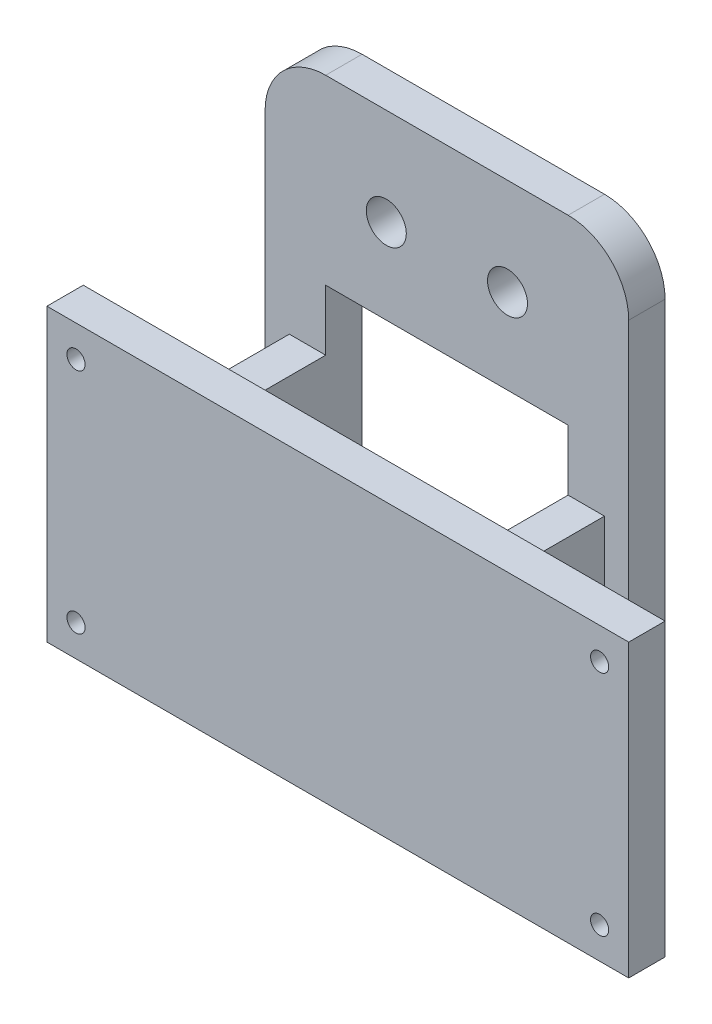
SolidWorks part; units mm, degrees
ref_plane "前视基准面" through (0, 0, 0) normal (0, 0, 1) x (1, 0, 0)
ref_plane "上视基准面" through (0, 0, 0) normal (0, 1, 0) x (1, 0, 0)
ref_plane "右视基准面" through (0, 0, 0) normal (1, 0, 0) x (0, 0, -1)
sketch "草图1" plane through (0, 0, 0) normal (0, 0, 1) x (1, 0, 0)
  line L0 (-9.1846, -30.6462) -> (20.8154, -30.6462)
  line L1 (-9.1846, 4.3538) -> (20.8154, 4.3538)
  line L2 (-9.1846, 4.3538) -> (-9.1846, -30.6462)
  line L4 (20.8154, 4.3538) -> (20.8154, -30.6462)
  circle A0 centre (0.8154, -3.6462) radius 1.65
  circle A1 centre (10.8154, -3.6462) radius 1.65
  dimension "D3" = 3.3
  dimension "D4" = 3.3
  dimension "D5" = 10
  dimension "D6" = 10
  dimension "D8" = 8
  dimension "D9" = 8
  dimension "D1" = 30
  dimension "D2" = 35
extrude "凸台-拉伸1" add sketch "草图1" along normal blind 3
sketch "草图2" plane through (0, 0, 3) normal (0, 0, 1) x (1, 0, 0)
  line L0 (-9.1846, 4.3538) -> (-9.1846, -30.6462) construction
  line L5 (20.8154, 4.3538) -> (-9.1846, 4.3538) construction
  line L6 (-9.1846, -30.6462) -> (20.8154, -30.6462) construction
  line L7 (-4.1846, -30.6462) -> (15.8154, -30.6462)
  line L8 (-4.1846, -30.6462) -> (-4.1846, -10.6462)
  line L9 (-4.1846, -10.6462) -> (15.8154, -10.6462)
  line L10 (15.8154, -30.6462) -> (15.8154, -10.6462)
  line L11 (5.8154, 4.3538) -> (5.8154, -30.6462) construction
  line L12 (-9.1846, -0.6462) -> (-9.1846, 4.3538)
  line L13 (-9.1846, 4.3538) -> (-4.1846, 4.3538)
  line L14 (20.8154, -0.6462) -> (20.8154, 4.3538)
  line L15 (20.8154, 4.3538) -> (15.8154, 4.3538)
  arc A0 (-9.1846, -0.6462) -> (-4.1846, 4.3538) centre (-4.1846, -0.6462) cw
  arc A1 (20.8154, -0.6462) -> (15.8154, 4.3538) centre (15.8154, -0.6462) ccw
  dimension "D1" = 5
  dimension "D2" = 5
  dimension "D3" = 5
  dimension "D4" = 20
  dimension "D5" = 20
  dimension "D6" = 5
extrude "切除-拉伸1" cut sketch "草图2" against normal blind 6
sketch "草图3" plane through (0, 0, 3) normal (0, 0, 1) x (1, 0, 0)
  line L1 (-4.1846, -30.6462) -> (-7.1846, -30.6462)
  line L2 (-4.1846, -30.6462) -> (-4.1846, -15.6462)
  line L3 (-4.1846, -15.6462) -> (-7.1846, -15.6462)
  line L4 (-7.1846, -30.6462) -> (-7.1846, -15.6462)
  line L5 (15.8154, -30.6462) -> (18.8154, -30.6462)
  line L6 (15.8154, -30.6462) -> (15.8154, -15.6462)
  line L7 (15.8154, -15.6462) -> (18.8154, -15.6462)
  line L8 (18.8154, -30.6462) -> (18.8154, -15.6462)
  dimension "D1" = 15
  dimension "D2" = 3
  dimension "D3" = 3
  dimension "D4" = 15
extrude "凸台-拉伸2" add sketch "草图3" along normal blind 6
sketch "草图4" plane through (0, 0, 9) normal (0, 0, 1) x (1, 0, 0)
  line L0 (-7.1846, -15.6462) -> (-7.1846, -30.6462) construction
  line L1 (-18.1846, -14.6462) -> (29.8154, -14.6462)
  line L2 (-18.1846, -14.6462) -> (-18.1846, -38.6462)
  line L3 (-18.1846, -38.6462) -> (29.8154, -38.6462)
  line L4 (29.8154, -14.6462) -> (29.8154, -38.6462)
  line L5 (18.8154, -30.6462) -> (18.8154, -15.6462) construction
  line L6 (-4.1846, -15.6462) -> (-7.1846, -15.6462) construction
  dimension "D1" = 48
  dimension "D2" = 26
  dimension "D3" = 11
  dimension "D4" = 24
  dimension "D5" = 1
extrude "凸台-拉伸3" add sketch "草图4" along normal blind 3
sketch "草图6" plane through (0, 0, 12) normal (0, 0, 1) x (1, 0, 0)
  line L0 (5.8154, -14.6462) -> (5.8154, -38.6462) construction
  line L1 (29.8154, -14.6462) -> (-18.1846, -14.6462) construction
  line L2 (-18.1846, -38.6462) -> (29.8154, -38.6462) construction
  line L4 (-17.0346, -37.2962) -> (28.6654, -37.2962) construction
  line L5 (-17.0346, -37.2962) -> (-17.0346, -15.9962) construction
  line L6 (-17.0346, -15.9962) -> (28.6654, -15.9962) construction
  line L7 (28.6654, -37.2962) -> (28.6654, -15.9962) construction
  line L8 (-17.0346, -37.2962) -> (28.6654, -15.9962) construction
  line L9 (-17.0346, -15.9962) -> (28.6654, -37.2962) construction
  circle A0 centre (-15.7846, -17.2462) radius 0.75
  circle A1 centre (-15.7846, -36.0462) radius 0.75
  circle A2 centre (27.4154, -36.0462) radius 0.75
  circle A3 centre (27.4154, -17.2462) radius 0.75
  point P6 (5.8154, -26.6462)
  dimension "D3" = 1.25
  dimension "D4" = 1.5
  dimension "D6" = 1.5
  dimension "D7" = 1.25
  dimension "D8" = 1.25
  dimension "D1" = 21.3
  dimension "D2" = 45.7
  dimension "D5" = 1.25
extrude "切除-拉伸2" cut sketch "草图6" against normal blind 5
